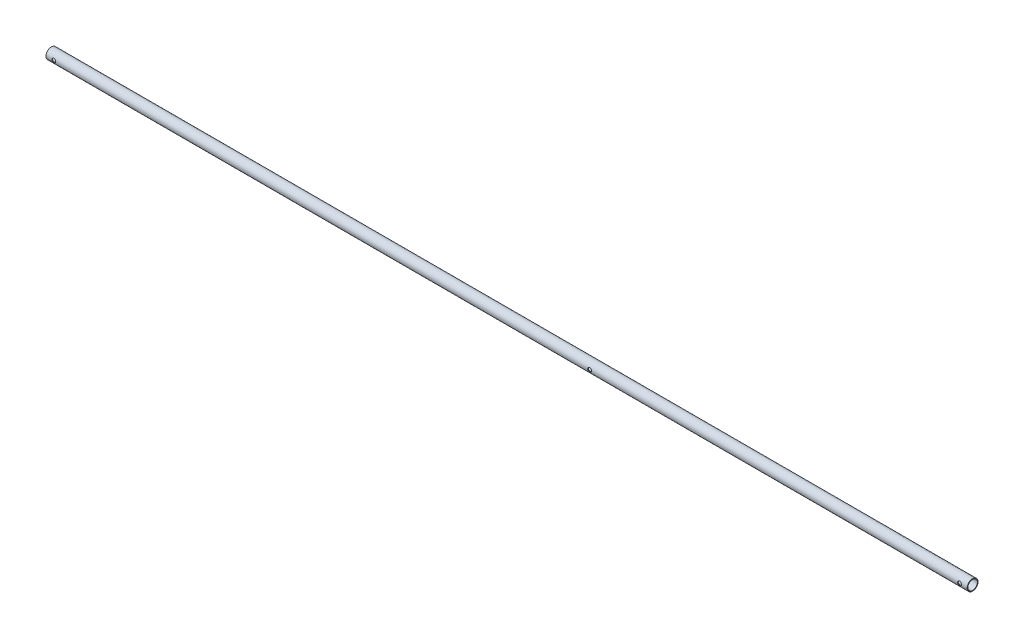
SolidWorks part; units mm, degrees
material "Galvanized Steel"
ref_plane "Front Plane" through (0, 0, 0) normal (0, 0, 1) x (1, 0, 0)
ref_plane "Top Plane" through (0, 0, 0) normal (0, 1, 0) x (1, 0, 0)
ref_plane "Right Plane" through (0, 0, 0) normal (1, 0, 0) x (0, 0, -1)
sketch "Sketch1" plane through (0, 0, 0) normal (1, 0, 0) x (0, 0, -1)
  circle A0 centre (0, 0) radius 7.8994
  circle A1 centre (0, 0) radius 8.9662
  dimension "D1" = 15.7988
  dimension "D2" = 17.9324
extrude "Boss-Extrude1" add sketch "Sketch1" along normal blind 1524
sketch "Sketch2" plane through (0, 0, 0) normal (0, 0, 1) x (1, 0, 0)
  line L0 (0, 8.9662) -> (0, -8.9662) construction
  line L1 (1524, -8.9662) -> (1524, 8.9662) construction
  circle A0 centre (1511.3, 0) radius 3.175
  circle A2 centre (12.7, 0) radius 3.175
  circle A3 centre (899.3378, 0) radius 3.175
  dimension "D1" = 886.6378
  dimension "D3" = 12.7
  dimension "D2" = 12.7
extrude "Cut-Extrude1" cut sketch "Sketch2" against normal through all and the other way through all
